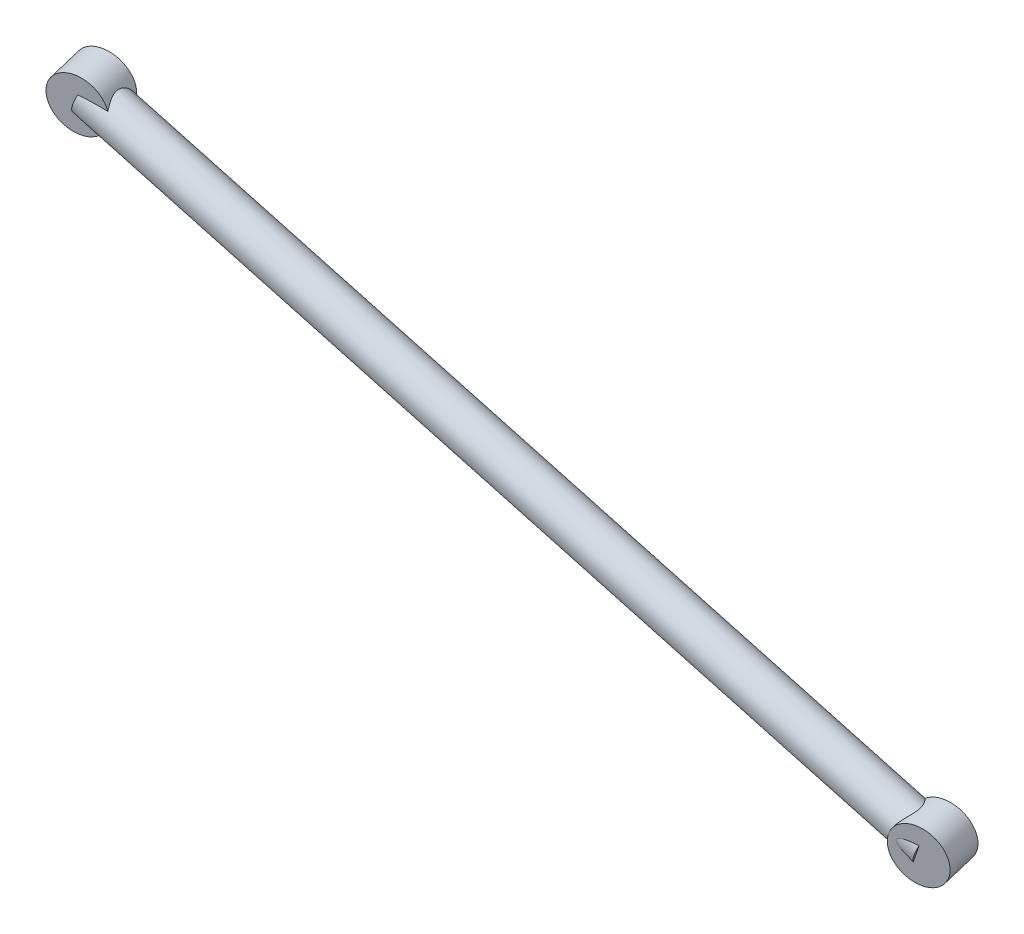
SolidWorks part; units mm, degrees
ref_plane "Plano frontal" through (0, 0, 0) normal (0, 0, 1) x (1, 0, 0)
ref_plane "Plano superior" through (0, 0, 0) normal (0, 1, 0) x (1, 0, 0)
ref_plane "Plano direito" through (0, 0, 0) normal (1, 0, 0) x (0, 0, -1)
sketch3d "SUSP_FR_tie_rod_eixo"
  line L0 (270, -90.4, -82.3915) -> (590.2935, -204.9905, -103.7504)
sweep "SUSP_FR_tie_rod" add path "SUSP_FR_tie_rod_eixo" circular profile diameter 16 parameters "D3"=16
sketch3d "SUSP_FR_tie_rod_rod_end_in_eixo"
  line L0 (271.2111, -91.0009, -75.5233) -> (268.7889, -89.7991, -89.2597)
sweep "SUSP_FR_tie_rod_rod_end_in" add path "SUSP_FR_tie_rod_rod_end_in_eixo" circular profile diameter 22 parameters "D3"=22
sketch3d "SUSP_FR_tie_rod_rod_end_out_eixo"
  line L0 (591.5046, -205.5914, -96.8822) -> (589.0825, -204.3896, -110.6186)
sweep "SUSP_FR_tie_rod_rod_end_out" add path "SUSP_FR_tie_rod_rod_end_out_eixo" circular profile diameter 22 parameters "D3"=22
sketch3d "REF_SKETCH"
  line L0 (266, -92.8, -84.1915) -> (274, -88, -80.5915)
  line L1 (272.4, -93.4, -85.5915) -> (267.6, -87.4, -79.1915)
  line L2 (586.2935, -207.3905, -105.5504) -> (594.2935, -202.5905, -101.9504)
  line L3 (592.6935, -207.9905, -106.9504) -> (587.8935, -201.9905, -100.5504)
ref_point "P_IN"
ref_point "P_OUT"
